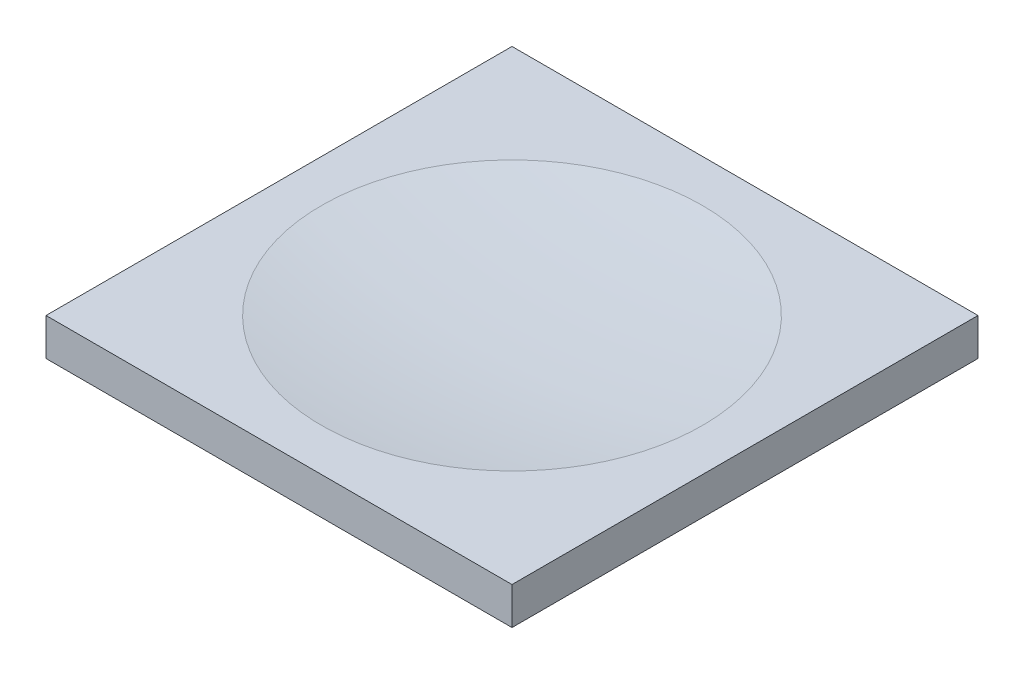
SolidWorks part; units mm, degrees
ref_plane "Plan de face" through (0, 0, 0) normal (0, 0, 1) x (1, 0, 0)
ref_plane "Plan de dessus" through (0, 0, 0) normal (0, 1, 0) x (1, 0, 0)
ref_plane "Plan de droite" through (0, 0, 0) normal (1, 0, 0) x (0, 0, -1)
sketch "Esquisse3" plane through (0, 0, 0) normal (0, 0, 1) x (1, 0, 0)
  line L0 (0, 0) -> (20.44, 0)
  line L1 (0, 0) -> (0, 4)
  line L2 (20.44, 0) -> (20.44, 2.5)
  arc A2 (0, 4) -> (20.44, 2.5) centre (20.439, 142.5003) ccw
  point P7 (20.2763, 2.5)
  point P8 (16.6477, 2.1448)
revolve "Révolution2" add sketch "Esquisse3" angle 360 about L2
sketch "Esquisse4" plane through (0, 0, 0) normal (0, -1, 0) x (-1, 0, 0)
  line L0 (-20.44, 20.44) -> (-20.44, 25)
  line L1 (-45.44, -25) -> (4.56, -25)
  line L2 (-40.88, 0) -> (-45.44, 0)
  line L3 (-20.44, -20.44) -> (-20.44, -25)
  line L4 (4.56, 25) -> (-45.44, 25)
  line L5 (-45.44, 25) -> (-45.44, -25)
  line L6 (4.56, -25) -> (4.56, 25)
  line L7 (0, 0) -> (4.56, 0)
  circle A1 centre (-20.44, 0) radius 20.44
extrude "Boss.-Extru.1" add sketch "Esquisse4" against normal blind 4 contours A1 | L6 L4 L5 L1
